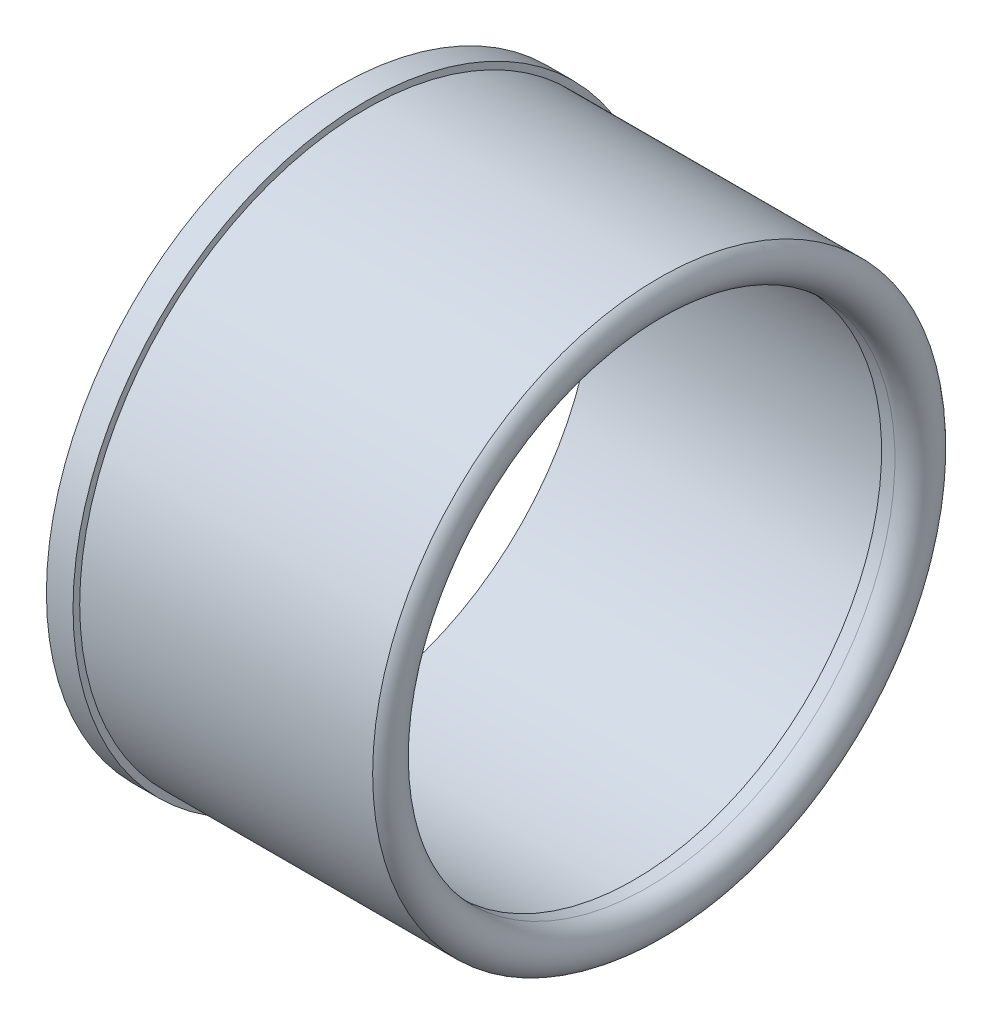
SolidWorks part; units mm, degrees
ref_plane "Front Plane" through (0, 0, 0) normal (0, 0, 1) x (1, 0, 0)
ref_plane "Top Plane" through (0, 0, 0) normal (0, 1, 0) x (1, 0, 0)
ref_plane "Right Plane" through (0, 0, 0) normal (1, 0, 0) x (0, 0, -1)
ref_plane "Plane1" through (0, 0, 0) normal (0, 0, -1) x (-1, 0, 0)
sketch "Sketch1" plane through (0, 0, 0) normal (0, 0, -1) x (-1, 0, 0)
  line L0 (-11.9728, 0.7667) -> (-11.9728, 1.0167)
  line L1 (-11.9728, 1.0167) -> (-0.9121, 1.0167)
  line L2 (-0.9121, 1.0167) -> (-0.9121, 2.4667)
  line L3 (-0.9121, 2.4667) -> (-1.9121, 2.4667)
  line L4 (-1.9121, 2.4667) -> (-1.9121, 2.2167)
  line L5 (-1.9121, 2.2167) -> (-12.9121, 2.2167)
  line L6 (-12.4728, 0.7667) -> (-11.9728, 0.7667)
  line L7 (-12.1757, -8.5333) -> (0.2029, -8.5333) construction
  arc A0 (-12.9121, 2.2167) -> (-12.4728, 0.7667) centre (-12.4728, 1.5583) ccw
  dimension "D1" = 11
  dimension "D2" = 1.45
  dimension "D3" = 0.25
  dimension "D4" = 0.25
  dimension "D5" = 19.1
  dimension "D6" = 1
  dimension "D7" = 0.5
revolve "Revolve1" add sketch "Sketch1" angle 360 about L7
